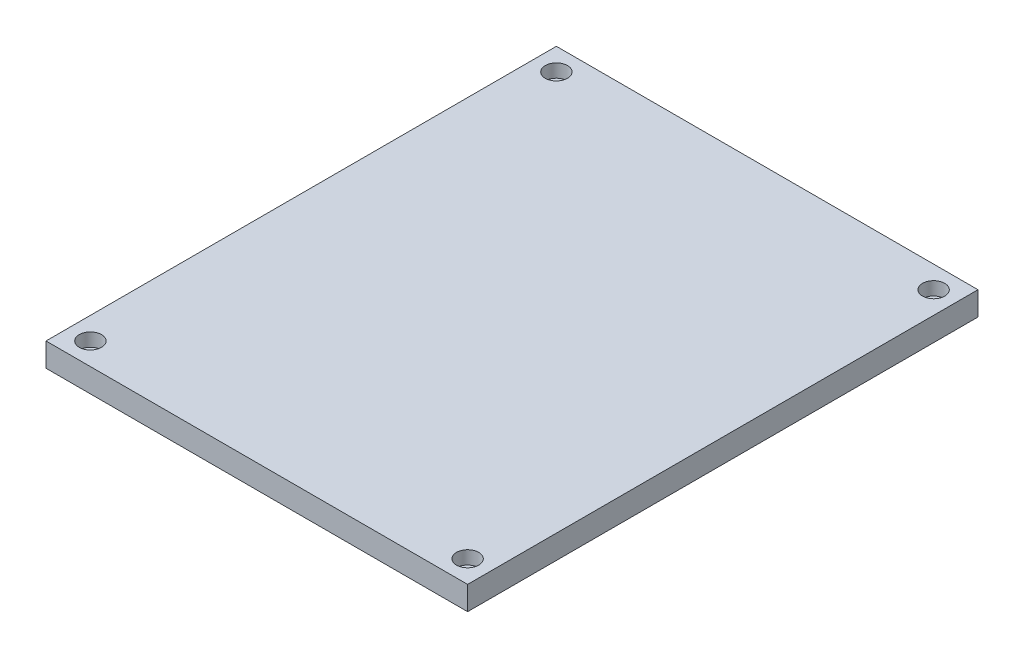
SolidWorks part; units mm, degrees
ref_plane "Front Plane" through (0, 0, 0) normal (0, 0, 1) x (1, 0, 0)
ref_plane "Top Plane" through (0, 0, 0) normal (0, 1, 0) x (1, 0, 0)
ref_plane "Right Plane" through (0, 0, 0) normal (1, 0, 0) x (0, 0, -1)
sketch "Sketch1" plane through (0, 0, 0) normal (0, 1, 0) x (1, 0, 0)
  line L0 (0, 0) -> (0, 172.5)
  line L1 (0, 172.5) -> (142.5, 172.5)
  line L2 (142.5, 172.5) -> (142.5, 0)
  line L3 (142.5, 0) -> (0, 0)
  dimension "D1" = 172.5
  dimension "D2" = 142.5
extrude "Boss-Extrude1" add sketch "Sketch1" along normal mid plane 8
sketch "Sketch2" plane through (0, 4, 0) normal (0, 1, 0) x (1, 0, 0)
  line L0 (142.5, 172.5) -> (0, 172.5) construction
  line L1 (0, 172.5) -> (0, 0) construction
  line L2 (142.5, 0) -> (142.5, 172.5) construction
  line L3 (0, 0) -> (142.5, 0) construction
  circle A0 centre (7.5, 165) radius 2.25
  circle A1 centre (135, 165) radius 2.25
  circle A2 centre (135, 7.5) radius 2.25
  circle A3 centre (7.5, 7.5) radius 2.25
  dimension "D1" = 4.5
  dimension "D2" = 7.5
  dimension "D3" = 7.5
  dimension "D4" = 7.5
  dimension "D5" = 7.5
extrude "Cut-Extrude1" cut sketch "Sketch2" against normal through all both and the other way through all
sketch "Sketch3" plane through (0, 4, 0) normal (0, 1, 0) x (1, 0, 0)
  circle A0 centre (7.5, 165) radius 3.75
  circle A1 centre (135, 165) radius 3.75
  circle A2 centre (135, 7.5) radius 3.75
  circle A3 centre (7.5, 7.5) radius 3.75
  dimension "D1" = 7.5
extrude "Cut-Extrude2" cut sketch "Sketch3" against normal blind 4.5 and the other way through all
